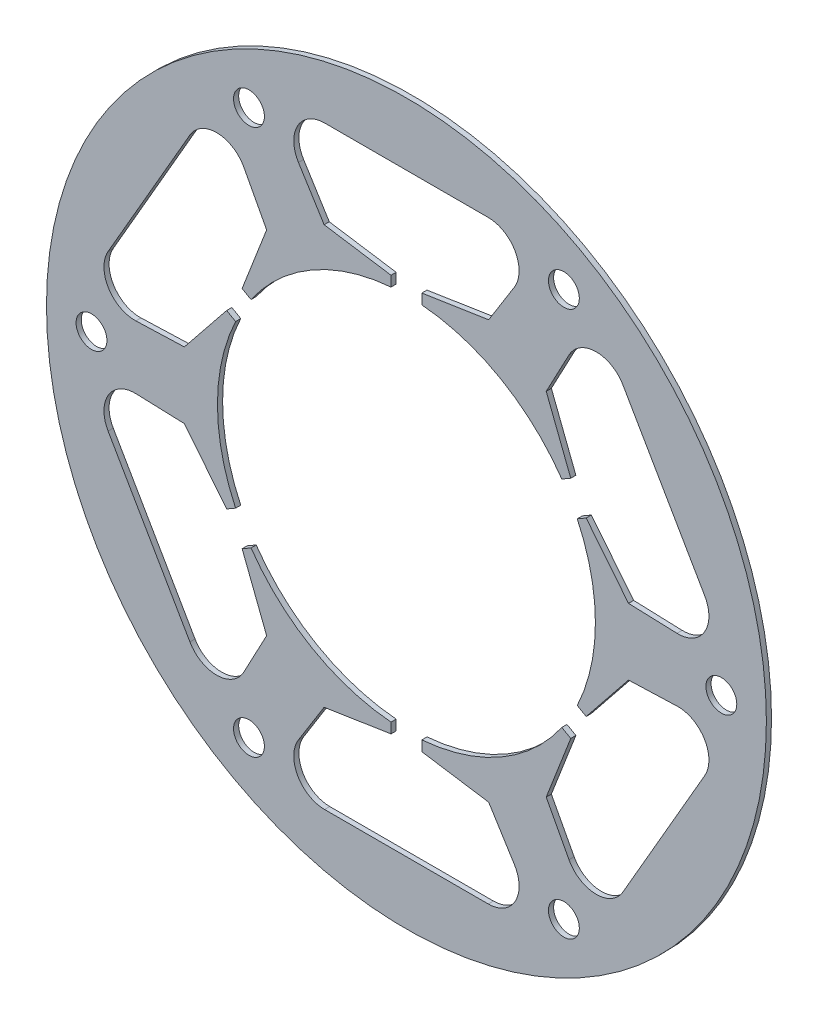
SolidWorks part; units mm, degrees
ref_plane "Ön Düzlem" through (0, 0, 0) normal (0, 0, 1) x (1, 0, 0)
ref_plane "Üst Düzlem" through (0, 0, 0) normal (0, 1, 0) x (1, 0, 0)
ref_plane "Sağ Düzlem" through (0, 0, 0) normal (1, 0, 0) x (0, 0, -1)
sketch "Çizim1" plane through (0, 0, 0) normal (0, 0, 1) x (1, 0, 0)
  line L0 (-1.5, 18.3137) -> (-1.5, 19.3137)
  line L1 (1.5, 18.3137) -> (1.5, 19.3137)
  line L2 (1.5, 19.3137) -> (8, 20.3137)
  line L3 (-1.5, 19.3137) -> (-8, 20.3137)
  line L4 (8, 20.3137) -> (10.5, 24.3137)
  line L5 (-8, 20.3137) -> (-10.5, 24.3137)
  line L6 (-7.956, 28.9037) -> (7.956, 28.9037)
  line L7 (13.5922, 17.085) -> (15.8063, 21.2501)
  line L8 (15.9761, 10.9559) -> (13.5922, 17.085)
  line L9 (15.1101, 10.4559) -> (15.9761, 10.9559)
  line L10 (16.6101, 7.8578) -> (17.4761, 8.3578)
  line L11 (17.4761, 8.3578) -> (21.5922, 3.2286)
  line L12 (21.5922, 3.2286) -> (26.3063, 3.0636)
  line L13 (21.0533, 21.3419) -> (29.0093, 7.5617)
  line L14 (21.5922, -3.2286) -> (26.3063, -3.0636)
  line L15 (17.4761, -8.3578) -> (21.5922, -3.2286)
  line L16 (16.6101, -7.8578) -> (17.4761, -8.3578)
  line L17 (15.1101, -10.4559) -> (15.9761, -10.9559)
  line L18 (15.9761, -10.9559) -> (13.5922, -17.085)
  line L19 (13.5922, -17.085) -> (15.8063, -21.2501)
  line L20 (29.0093, -7.5617) -> (21.0533, -21.3419)
  line L21 (8, -20.3137) -> (10.5, -24.3137)
  line L22 (1.5, -19.3137) -> (8, -20.3137)
  line L23 (1.5, -18.3137) -> (1.5, -19.3137)
  line L24 (-1.5, -18.3137) -> (-1.5, -19.3137)
  line L25 (-1.5, -19.3137) -> (-8, -20.3137)
  line L26 (-8, -20.3137) -> (-10.5, -24.3137)
  line L27 (7.956, -28.9037) -> (-7.956, -28.9037)
  line L28 (-13.5922, -17.085) -> (-15.8063, -21.2501)
  line L29 (-15.9761, -10.9559) -> (-13.5922, -17.085)
  line L30 (-15.1101, -10.4559) -> (-15.9761, -10.9559)
  line L31 (-16.6101, -7.8578) -> (-17.4761, -8.3578)
  line L32 (-17.4761, -8.3578) -> (-21.5922, -3.2286)
  line L33 (-21.5922, -3.2286) -> (-26.3063, -3.0636)
  line L34 (-21.0533, -21.3419) -> (-29.0093, -7.5617)
  line L35 (-21.5922, 3.2286) -> (-26.3063, 3.0636)
  line L36 (-17.4761, 8.3578) -> (-21.5922, 3.2286)
  line L37 (-16.6101, 7.8578) -> (-17.4761, 8.3578)
  line L38 (-15.1101, 10.4559) -> (-15.9761, 10.9559)
  line L39 (-15.9761, 10.9559) -> (-13.5922, 17.085)
  line L40 (-13.5922, 17.085) -> (-15.8063, 21.2501)
  line L41 (-29.0093, 7.5617) -> (-21.0533, 21.3419)
  circle A0 centre (0, 0) radius 35
  arc A1 (-16.6101, 7.8578) -> (-16.6101, -7.8578) centre (0, 0) ccw
  arc A2 (-7.956, 28.9037) -> (-10.5, 24.3137) centre (-7.956, 25.9037) ccw
  arc A3 (10.5, 24.3137) -> (7.956, 28.9037) centre (7.956, 25.9037) ccw
  arc A4 (26.3063, 3.0636) -> (29.0093, 7.5617) centre (26.4112, 6.0617) ccw
  arc A5 (21.0533, 21.3419) -> (15.8063, 21.2501) centre (18.4552, 19.8419) ccw
  arc A6 (15.8063, -21.2501) -> (21.0533, -21.3419) centre (18.4552, -19.8419) ccw
  arc A7 (29.0093, -7.5617) -> (26.3063, -3.0636) centre (26.4112, -6.0617) ccw
  arc A8 (-10.5, -24.3137) -> (-7.956, -28.9037) centre (-7.956, -25.9037) ccw
  arc A9 (7.956, -28.9037) -> (10.5, -24.3137) centre (7.956, -25.9037) ccw
  arc A10 (-26.3063, -3.0636) -> (-29.0093, -7.5617) centre (-26.4112, -6.0617) ccw
  arc A11 (-21.0533, -21.3419) -> (-15.8063, -21.2501) centre (-18.4552, -19.8419) ccw
  arc A12 (-15.8063, 21.2501) -> (-21.0533, 21.3419) centre (-18.4552, 19.8419) ccw
  arc A13 (-29.0093, 7.5617) -> (-26.3063, 3.0636) centre (-26.4112, 6.0617) ccw
  arc A14 (-15.1101, -10.4559) -> (-1.5, -18.3137) centre (0, 0) ccw
  arc A15 (1.5, -18.3137) -> (15.1101, -10.4559) centre (0, 0) ccw
  arc A16 (16.6101, -7.8578) -> (16.6101, 7.8578) centre (0, 0) ccw
  arc A17 (15.1101, 10.4559) -> (1.5, 18.3137) centre (0, 0) ccw
  arc A18 (-1.5, 18.3137) -> (-15.1101, 10.4559) centre (0, 0) ccw
  circle A19 centre (-15.3101, 26.5179) radius 4.3797 construction
  circle A20 centre (-15.3101, 26.5179) radius 1.5
  circle A21 centre (15.3101, 26.5179) radius 1.5
  circle A22 centre (30.6203, 0) radius 1.5
  circle A23 centre (15.3101, -26.5179) radius 1.5
  circle A24 centre (-15.3101, -26.5179) radius 1.5
  circle A25 centre (-30.6203, 0) radius 1.5
  point P79 (0, 0)
  point P80 (-30.695, 2.1095)
  point P81 (0, 0)
  point P82 (0, 0)
  point P93 (0, 0)
  dimension "D1" = 70
  dimension "D2" = 36.75
  dimension "D15" = 6
  dimension "D16" = 6
  dimension "D18" = 3
  dimension "D3" = 3
  dimension "D4" = 1.5
  dimension "D5" = 1
  dimension "D6" = 1
  dimension "D7" = 1
  dimension "D8" = 1
  dimension "D9" = 16
  dimension "D10" = 8
  dimension "D11" = 4
  dimension "D12" = 4
  dimension "D13" = 21
  dimension "D14" = 10.5
  dimension "D17" = 6
  dimension "D19" = 6
extrude "Yükseklik-Ekstrüzyon1" add sketch "Çizim1" along normal blind 0.5
